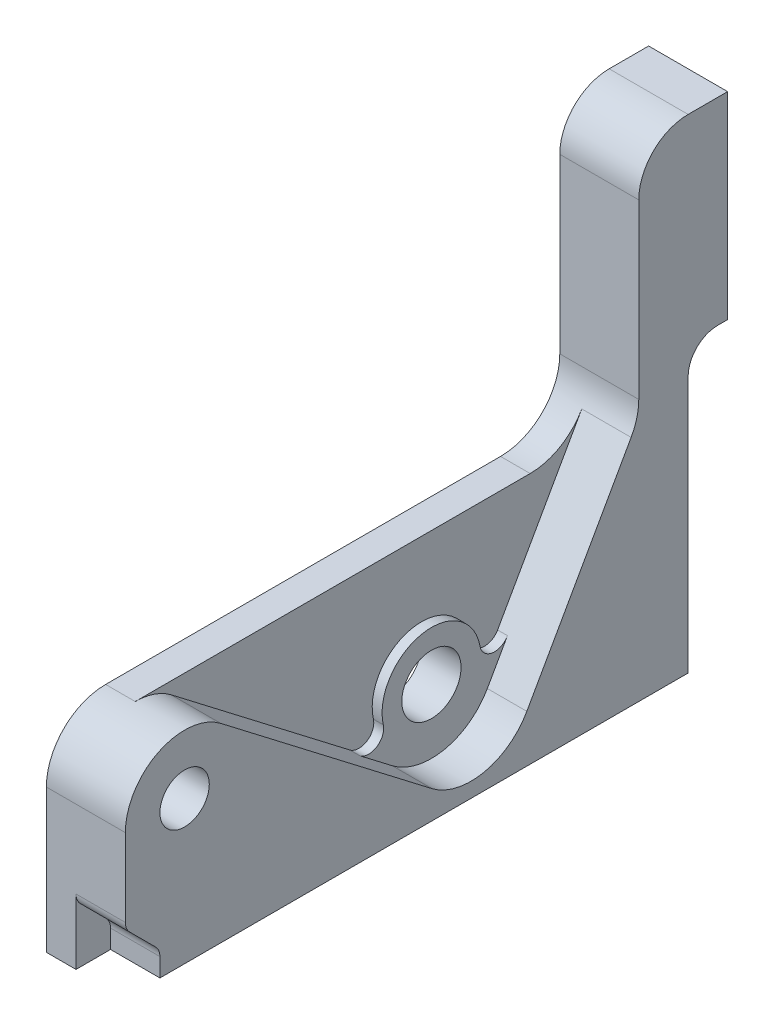
SolidWorks part; units mm, degrees
material "POM Acetal Copolymer"
ref_plane "Front Plane" through (0, 0, 0) normal (0, 0, 1) x (1, 0, 0)
ref_plane "Top Plane" through (0, 0, 0) normal (0, 1, 0) x (1, 0, 0)
ref_plane "Right Plane" through (0, 0, 0) normal (1, 0, 0) x (0, 0, -1)
sketch "Sketch1" plane through (0, 0, 0) normal (1, 0, 0) x (0, 0, -1)
  line L1 (0, 0) -> (61, 0)
  line L2 (0, 0) -> (0, 49)
  line L3 (0, 49) -> (61, 49)
  line L4 (61, 0) -> (61, 49)
  circle A0 centre (6, 14.5) radius 2.5
  circle A1 centre (35, 8) radius 3
  dimension "D1" = 6
  dimension "D2" = 5
  dimension "D3" = 14.5
  dimension "D4" = 6
  dimension "D5" = 8
  dimension "D6" = 35
  dimension "D7" = 61
  dimension "D8" = 49
extrude "Boss-Extrude1" add sketch "Sketch1" along normal blind 8
sketch "Sketch3" plane through (8, 0, 0) normal (1, 0, 0) x (0, 0, -1)
  line L57 (61, 0) -> (57, 0)
  line L58 (61, 0) -> (61, 29)
  line L59 (61, 29) -> (57, 29)
  line L60 (57, 0) -> (57, 29)
  dimension "D1" = 29
  dimension "D2" = 4
extrude "Cut-Extrude2" cut sketch "Sketch3" against normal up to next
fillet "Fillet2" radius 3 1 edges at (4, 29, -57)
hole_wizard "Tap Drill for M3 Tap1" positions "Sketch5" profile "Sketch4" hole size "M3" standard "ISO"
sketch "Sketch5" plane through (0, 0, 0) normal (0, -1, 0) x (-1, 0, 0)
  line L0 (0, 0) -> (0, 57) construction
  line L1 (-8, 0) -> (0, 0) construction
  point P0 (-4, 48)
  point P2 (-4, 12)
  dimension "D1" = 4
  dimension "D2" = 12
  dimension "D3" = 36
sketch "Sketch4" plane through (4, 0, -48) normal (1, 0, 0) x (0, 0, -1)
  line L0 (0, 0) -> (0, 10.7511)
  line L1 (0, 10.7511) -> (1.25, 10)
  line L2 (1.25, 10) -> (1.25, 0)
  line L5 (1.25, 0) -> (0, 0)
  line L10 (0, 10.7511) -> (-1.25, 10) construction
  line L11 (0, -6.35) -> (0, 107.95) construction
  dimension "Hole Dia." = 2.5
  dimension "Hole Depth" = 10
  dimension "Drill Angle" = 118
hole_wizard "Tap Drill for M3 Tap2" positions "Sketch8" profile "Sketch7" hole size "M3" standard "ISO"
sketch "Sketch8" plane through (0, 0, -61) normal (0, 0, -1) x (-1, 0, 0)
  line L0 (0, 29) -> (0, 49) construction
  line L2 (-8, 29) -> (0, 29) construction
  point P0 (-4, 44)
  point P2 (-4, 34)
  dimension "D1" = 4
  dimension "D2" = 10
  dimension "D3" = 5
sketch "Sketch7" plane through (4, 44, -61) normal (1, 0, 0) x (0, 1, 0)
  line L0 (0, 0) -> (0, 8.7511)
  line L1 (0, 8.7511) -> (1.25, 8)
  line L2 (1.25, 8) -> (1.25, 0)
  line L5 (1.25, 0) -> (0, 0)
  line L10 (0, 8.7511) -> (-1.25, 8) construction
  line L11 (0, -6.35) -> (0, 107.95) construction
  dimension "Hole Dia." = 2.5
  dimension "Hole Depth" = 8
  dimension "Drill Angle" = 118
sketch "Sketch9" plane through (8, 0, 0) normal (1, 0, 0) x (0, 0, -1)
  line L0 (6, 20.5) -> (46, 20.5)
  line L19 (52, 49) -> (52, 26.5)
  line L21 (0, 49) -> (0, 0) construction
  line L22 (52, 49) -> (0, 49)
  line L23 (0, 49) -> (0, 14.5)
  line L24 (0, 49) -> (0, 0) construction
  line L25 (61, 49) -> (0, 49) construction
  arc A0 (52, 26.5) -> (46, 20.5) centre (46, 26.5) cw
  arc A12 (0, 14.5) -> (6, 20.5) centre (6, 14.5) cw
  circle A16 centre (6, 14.5) radius 2.5 construction
  dimension "D1" = 52
extrude "Cut-Extrude3" cut sketch "Sketch9" against normal blind 8
sketch "Sketch13" plane through (8, 0, 0) normal (1, 0, 0) x (0, 0, -1)
  line L0 (52, 26.5) -> (52, 49) construction
  line L1 (9.653, 19.2598) -> (31.0425, 2.8436)
  line L2 (0, 14.5) -> (0, 26.5)
  line L3 (0, 26.5) -> (52, 26.5)
  line L4 (40.6626, 4.8087) -> (51.2271, 23.5542)
  line L5 (0, 14.5) -> (0, 0) construction
  line L6 (0, 6) -> (3.5, 2.5)
  line L7 (3.5, 2.5) -> (3.5, 0)
  line L8 (0, 0) -> (0, 6)
  line L9 (1.0251, 4.9749) -> (12.8536, 16.8034) construction
  line L10 (3.1464, 2.8536) -> (15.254, 14.9611) construction
  line L13 (0, 0) -> (57, 0) construction
  line L14 (3.5, 0) -> (0, 0)
  arc A0 (0, 14.5) -> (9.653, 19.2598) centre (6, 14.5) cw
  arc A1 (6, 20.5) -> (0, 14.5) centre (6, 14.5) ccw construction
  arc A2 (46, 20.5) -> (52, 26.5) centre (46, 26.5) ccw construction
  arc A3 (31.0425, 2.8436) -> (40.6626, 4.8087) centre (35, 8) ccw
  circle A5 centre (35, 8) radius 3 construction
  arc A6 (51.2271, 23.5542) -> (52, 26.5) centre (46, 26.5) ccw
  arc A7 (6, 20.5) -> (0, 14.5) centre (6, 14.5) ccw construction
  dimension "D1" = 6.5
  dimension "D4" = 3
  dimension "D6" = 3.5
  dimension "D8" = 6
  dimension "D9" = 0.5
  dimension "D10" = 45
extrude "Cut-Extrude4" cut sketch "Sketch13" against normal blind 5
sketch "Sketch14" plane through (3, 0, 0) normal (1, 0, 0) x (0, 0, -1)
  line L0 (9.653, 19.2598) -> (31.0425, 2.8436) construction
  line L1 (40.6626, 4.8087) -> (51.2271, 23.5542) construction
  line L2 (27.7477, 5.3723) -> (31.0425, 2.8436)
  line L3 (40.6626, 4.8087) -> (42.7018, 8.427)
  arc A0 (30.1238, 6.894) -> (39.9193, 8.8949) centre (35, 8) cw
  circle A1 centre (35, 8) radius 3
  circle A2 centre (35, 8) radius 3 construction
  arc A3 (30.1238, 6.894) -> (27.7477, 5.3723) centre (28.661, 6.5622) cw
  arc A4 (39.9193, 8.8949) -> (42.7018, 8.427) centre (41.395, 9.1634) ccw
  arc A5 (31.0425, 2.8436) -> (40.6626, 4.8087) centre (35, 8) ccw
  dimension "D1" = 1.5
  dimension "D2" = 5
extrude "Boss-Extrude2" add sketch "Sketch14" along normal blind 1
fillet "Fillet3" radius 5 1 edges at (4, 49, -52)
fillet "Fillet4" radius 1.5 2 edges at (5.5, 2.5, -3.5) (5.5, 6, 0)
